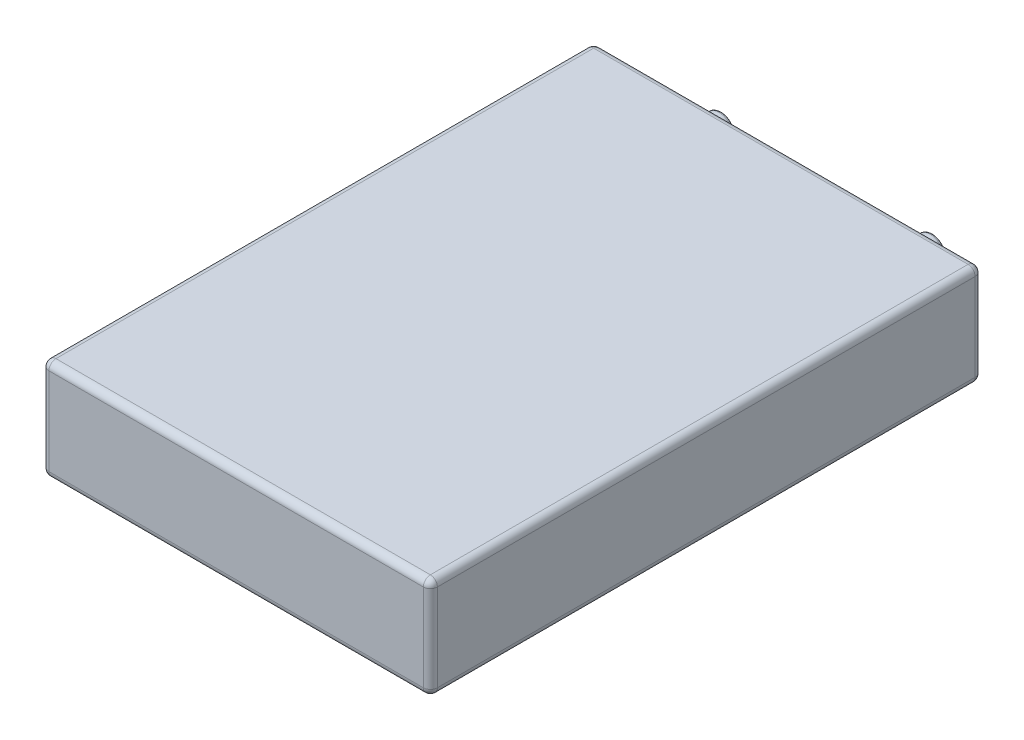
SolidWorks part; units mm, degrees
ref_plane "Ön Düzlem" through (0, 0, 0) normal (0, 0, 1) x (1, 0, 0)
ref_plane "Üst Düzlem" through (0, 0, 0) normal (0, 1, 0) x (1, 0, 0)
ref_plane "Sağ Düzlem" through (0, 0, 0) normal (1, 0, 0) x (0, 0, -1)
sketch "Sketch1" plane through (0, 0, 0) normal (0, 1, 0) x (1, 0, 0)
  line L1 (66.5, -98) -> (-66.5, -98)
  line L2 (69, -95.5) -> (69, 95.5)
  line L3 (66.5, 98) -> (-66.5, 98)
  line L4 (-69, -95.5) -> (-69, 95.5)
  line L5 (69, -98) -> (-69, 98) construction
  line L6 (69, 98) -> (-69, -98) construction
  arc A0 (-66.5, -98) -> (-69, -95.5) centre (-66.5, -95.5) cw
  arc A1 (66.5, -98) -> (69, -95.5) centre (66.5, -95.5) ccw
  arc A2 (69, 95.5) -> (66.5, 98) centre (66.5, 95.5) ccw
  arc A3 (-66.5, 98) -> (-69, 95.5) centre (-66.5, 95.5) ccw
  point P0 (0, 0)
  dimension "D3" = 2.5
  dimension "D1" = 138
  dimension "D2" = 196
extrude "Boss-Extrude1" add sketch "Sketch1" along normal blind 36
fillet "Fillet1" radius 2.5 16 edges at (0, 0, 98) (68.2678, 0, 97.2678) (69, 0, 0) (68.2678, 0, -97.2678) (0, 0, -98) (-68.2678, 0, -97.2678) (-69, 0, 0) (-68.2678, 0, 97.2678) (-69, 36, 0) (-68.2678, 36, -97.2678) (0, 36, -98) (68.2678, 36, -97.2678) (69, 36, 0) (68.2678, 36, 97.2678) (0, 36, 98) (-68.2678, 36, 97.2678)
sketch "Sketch2" plane through (0, 0, -98) normal (0, 0, -1) x (-1, 0, 0)
  line L0 (-66.5, 18) -> (66.5, 18) construction
  line L1 (-66.5, 33.5) -> (-66.5, 2.5) construction
  line L2 (66.5, 33.5) -> (66.5, 2.5) construction
  line L3 (0, 18) -> (0, 29.2197) construction
  circle A0 centre (-37.5, 18) radius 10
  circle A1 centre (37.5, 18) radius 10
  point P10 (0, 0)
  dimension "D2" = 20
  dimension "D1" = 75
extrude "Boss-Extrude2" add sketch "Sketch2" along normal blind 4
sketch "Sketch3" plane through (0, 0, -102) normal (0, 0, -1) x (-1, 0, 0)
  circle A0 centre (-37.5, 18) radius 5
  circle A2 centre (37.5, 18) radius 5
  dimension "D1" = 10
  dimension "D2" = 10
extrude "Boss-Extrude3" add sketch "Sketch3" along normal blind 10
fillet "Fillet2" radius 1 4 edges at (-47.5, 18, -102) (-42.5, 18, -112) (27.5, 18, -102) (32.5, 18, -112)
